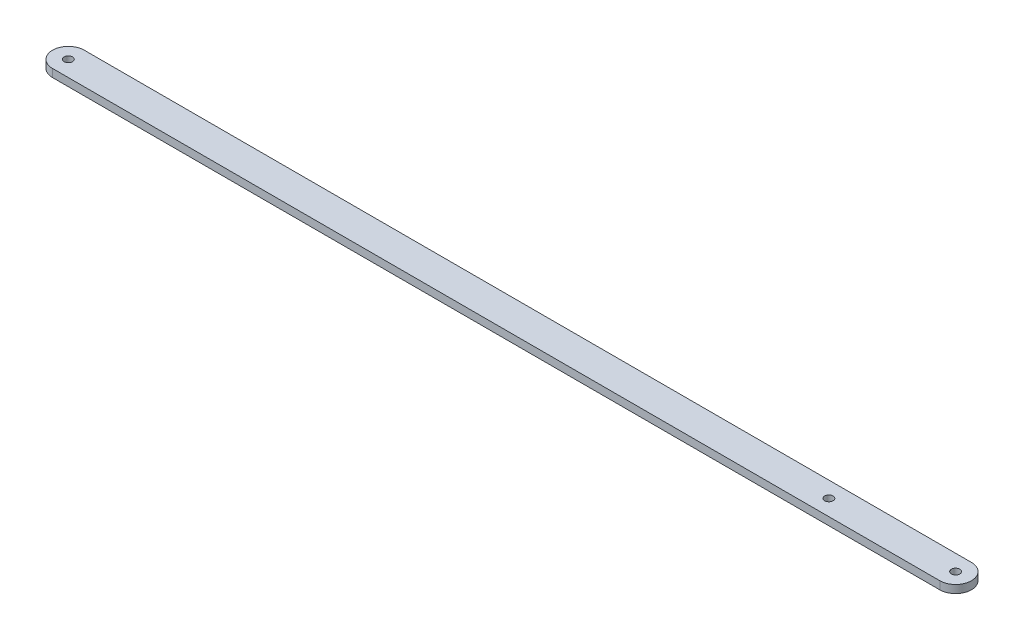
SolidWorks part; units mm, degrees
ref_plane "Front Plane" through (0, 0, 0) normal (0, 0, 1) x (1, 0, 0)
ref_plane "Top Plane" through (0, 0, 0) normal (0, 1, 0) x (1, 0, 0)
ref_plane "Right Plane" through (0, 0, 0) normal (1, 0, 0) x (0, 0, -1)
sketch "Sketch1" plane through (0, 0, 0) normal (0, 1, 0) x (1, 0, 0)
  line L0 (-355.6, 0) -> (355.6, 0) construction
  line L1 (-355.6, 12.7) -> (355.6, 12.7)
  line L2 (-355.6, -12.7) -> (355.6, -12.7)
  arc A0 (-355.6, 12.7) -> (-355.6, -12.7) centre (-355.6, 0) ccw
  arc A1 (355.6, -12.7) -> (355.6, 12.7) centre (355.6, 0) ccw
  circle A2 centre (355.6, 0) radius 3.3655
  circle A3 centre (254, 0) radius 3.3655
  circle A4 centre (-355.6, 0) radius 3.3655
  point P2 (0, 0)
  dimension "D3" = 6.731
  dimension "D5" = 6.731
  dimension "D6" = 6.731
  dimension "D1" = 711.2
  dimension "D2" = 25.4
  dimension "D4" = 609.6
extrude "Boss-Extrude1" add sketch "Sketch1" along normal blind 6.35
